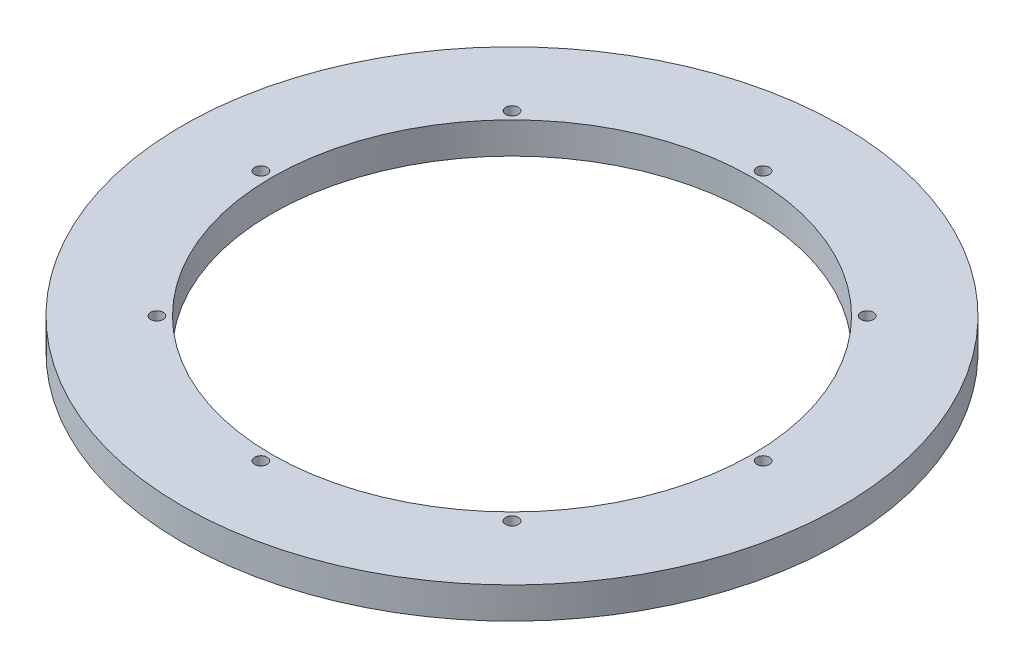
SolidWorks part; units mm, degrees
ref_plane "Front Plane" through (0, 0, 0) normal (0, 0, 1) x (1, 0, 0)
ref_plane "Top Plane" through (0, 0, 0) normal (0, 1, 0) x (1, 0, 0)
ref_plane "Right Plane" through (0, 0, 0) normal (1, 0, 0) x (0, 0, -1)
sketch "Sketch1" plane through (0, 0, 0) normal (1, 0, 0) x (0, 0, -1)
  line L0 (0, -3585.4219) -> (0, 175685.6755) construction
  line L2 (-315, 15) -> (-229.5, 15)
  line L3 (-315, 15) -> (-315, -15)
  line L4 (-315, -15) -> (-229.5, -15)
  line L5 (-229.5, 15) -> (-229.5, -15)
  line L6 (-315, 15) -> (-229.5, -15) construction
  line L7 (-315, -15) -> (-229.5, 15) construction
  point P1 (-272.25, 0)
  dimension "D1" = 459
  dimension "D2" = 85.5
  dimension "D3" = 30
revolve "Revolve1" add sketch "Sketch1" angle 360 about L0
sketch "Sketch2" plane through (0, 15, 0) normal (0, 1, 0) x (1, 0, 0)
  line L0 (0, -1000) -> (0, 49000) construction
  line L1 (-1000, 0) -> (49000, 0) construction
  circle A0 centre (0, 240) radius 6
  circle A1 centre (169.7056, 169.7056) radius 6
  circle A2 centre (240, 0) radius 6
  circle A3 centre (169.7056, -169.7056) radius 6
  circle A4 centre (0, -240) radius 6
  circle A5 centre (-169.7056, -169.7056) radius 6
  circle A6 centre (-240, 0) radius 6
  circle A7 centre (-169.7056, 169.7056) radius 6
  point P25 (0, 0)
  dimension "D2" = 12
  dimension "D1" = 240
  dimension "D3" = 8
extrude "Cut-Extrude1" cut sketch "Sketch2" against normal through all
